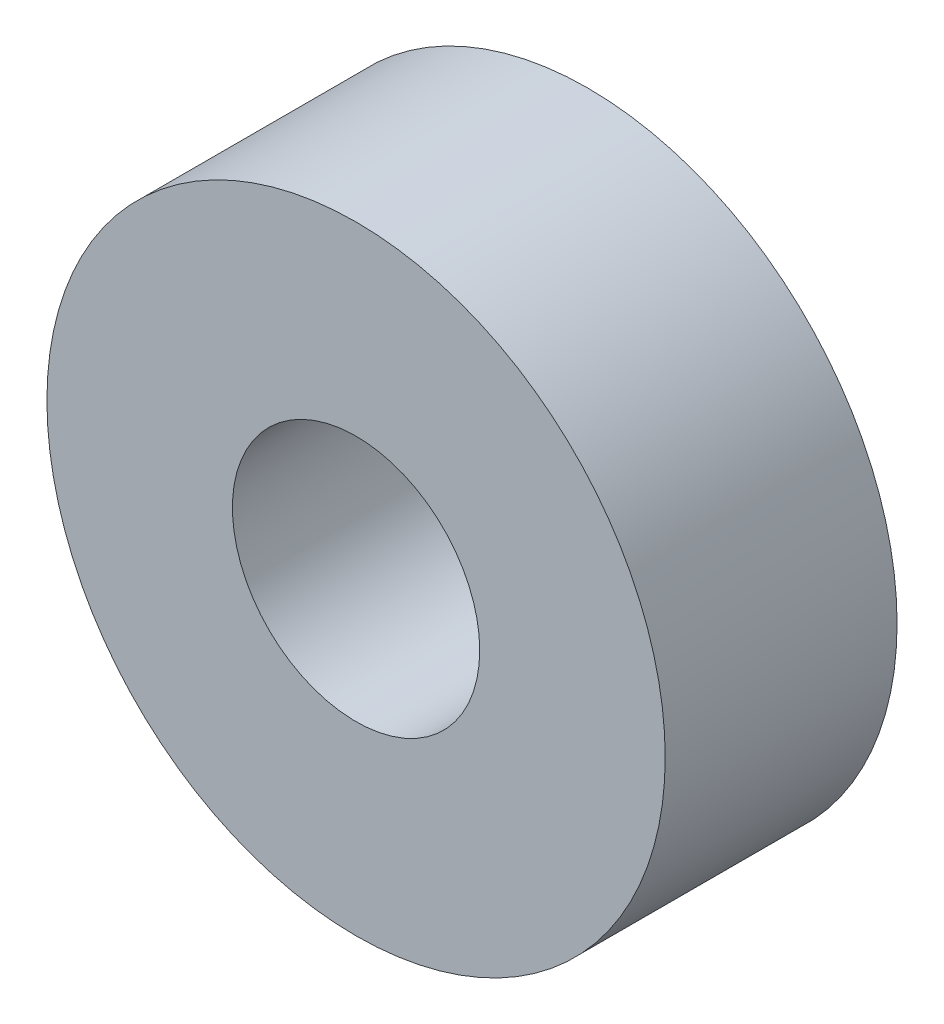
SolidWorks part; units mm, degrees
ref_plane "Front Plane" through (0, 0, 0) normal (0, 0, 1) x (1, 0, 0)
ref_plane "Top Plane" through (0, 0, 0) normal (0, 1, 0) x (1, 0, 0)
ref_plane "Right Plane" through (0, 0, 0) normal (1, 0, 0) x (0, 0, -1)
sketch "Sketch1" plane through (0, 0, 0) normal (0, 0, 1) x (1, 0, 0)
  circle A0 centre (0, 0) radius 4
  circle A1 centre (0, 0) radius 1.6
  dimension "OD" = 8
  dimension "ID" = 3.2
extrude "Extrude1" add sketch "Sketch1" along normal mid plane 3
sketch "Sketch2" plane through (0, 0, 0) normal (1, 0, 0) x (0, 0, -1)
  line L0 (-1.5, -1.6) -> (1.5, -1.6) construction
  line L3 (1.5, 1.6) -> (-1.5, 1.6) construction
  line L5 (-1.5, -1.6) -> (1.5, -1.6)
  line L6 (1.5, 1.6) -> (-1.5, 1.6)
sketch "Sketch4" plane through (0, 0, 1.5) normal (0, 0, 1) x (1, 0, 0)
  line L0 (0, 0) -> (-1.1314, 1.1314)
  line L1 (0, -1.1) -> (0, 1.1) construction
  circle A0 centre (0, 0) radius 1.6 construction
  dimension "D1" = 45
